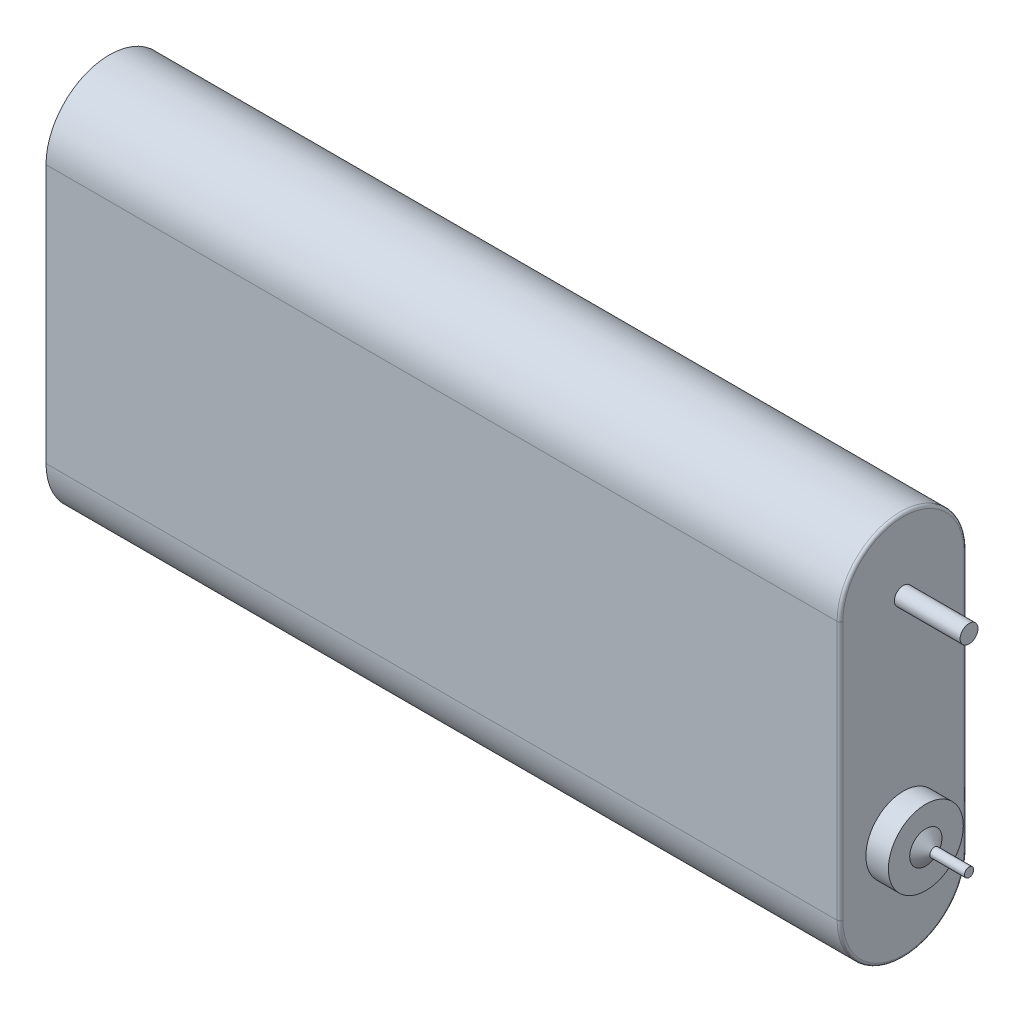
SolidWorks part; units mm, degrees
ref_plane "Front" through (0, 0, 0) normal (0, 0, 1) x (1, 0, 0)
ref_plane "Top" through (0, 0, 0) normal (0, 1, 0) x (1, 0, 0)
ref_plane "Right" through (0, 0, 0) normal (1, 0, 0) x (0, 0, -1)
ref_plane "Plane1" through (4.5212, 0, 0) normal (-1, 0, 0) x (0, -1, 0)
sketch "Sketch1" plane through (0, 0, 0) normal (-1, 0, 0) x (0, -1, 0)
  line L0 (5.7023, 2.794) -> (-5.7023, 2.794)
  line L1 (-5.7023, -2.794) -> (5.7023, -2.794)
  line L2 (5.7023, 0) -> (-5.7023, 0) construction
  arc A0 (-5.7023, 2.794) -> (-5.7023, -2.794) centre (-5.7023, 0) ccw
  arc A1 (5.7023, -2.794) -> (5.7023, 2.794) centre (5.7023, 0) ccw
  dimension "D1" = 2.794
  dimension "D2" = 11.4046
extrude "Boss-Extrude1" add sketch "Sketch1" against normal blind 34.9885
sketch "Sketch2" plane through (0, 0, 0) normal (0, 0, 1) x (1, 0, 0)
  line L0 (34.9885, 5.7404) -> (34.9885, 5.3467)
  line L1 (34.9885, 5.3467) -> (37.8841, 5.3467)
  line L2 (37.8841, 5.3467) -> (37.8841, 5.7404)
  line L3 (37.8841, 5.7404) -> (34.9885, 5.7404)
  line L4 (34.9885, 5.3467) -> (37.8841, 5.3467) construction
  line L6 (34.9885, -5.7023) -> (34.9885, 5.7023) construction
  line L7 (50, 0) -> (-50, 0) construction
  dimension "D1" = 2.8956
  dimension "D2" = 0.3937
  dimension "D3" = 5.3467
revolve "Revolve1" add sketch "Sketch2" angle 360 about L4
sketch "Sketch3" plane through (0, 0, 0) normal (0, 0, 1) x (1, 0, 0)
  line L0 (34.9885, -2.1082) -> (34.9885, -3.7592)
  line L1 (34.9885, -3.7592) -> (37.8841, -3.7592)
  line L2 (37.8841, -3.7592) -> (37.8841, -3.556)
  line L3 (37.8841, -3.556) -> (35.9791, -3.556)
  line L4 (35.9791, -3.556) -> (35.9791, -2.1082)
  line L5 (35.9791, -2.1082) -> (34.9885, -2.1082)
  line L6 (34.9885, -3.7592) -> (37.8841, -3.7592) construction
  line L8 (34.9885, -5.7023) -> (34.9885, 5.7023) construction
  line L9 (50, 0) -> (-50, 0) construction
  dimension "D1" = 0.9906
  dimension "D2" = 2.8956
  dimension "D3" = 0.2032
  dimension "D4" = 1.651
  dimension "D5" = 3.7592
revolve "Revolve2" add sketch "Sketch3" angle 360 about L6
fillet "Fillet1" radius 0.127 4 edges at (34.9885, 0, 2.794) (34.9885, -8.4963, 0) (34.9885, 8.4963, 0) (34.9885, 0, -2.794)
fillet "Fillet2" [suppressed] radius 0.508
sketch "Sketch4" plane through (37.8841, 0, 0) normal (1, 0, 0) x (0, 0, -1)
  circle A0 centre (0, -3.7592) radius 0.2032 construction
  circle A1 centre (0, 5.3467) radius 0.3937 construction
  circle A2 centre (0, -3.7592) radius 0.2032
  circle A3 centre (0, 5.3467) radius 0.3937
extrude "Cut-Extrude1" [suppressed] cut sketch "Sketch4" against normal blind 20
chamfer "Chamfer1" distance 0.508 distance2 0.381 1 edges at (35.9791, -3.7592, -0.2032)
